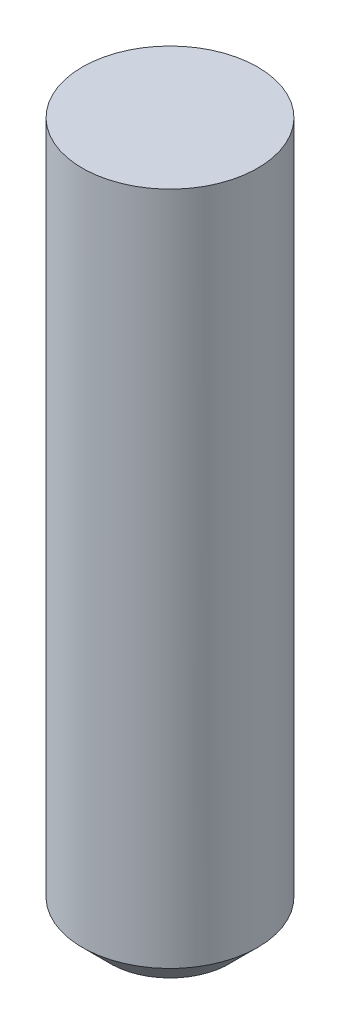
SolidWorks part; units mm, degrees
material "AISI 1020"
ref_plane "Front Plane" through (0, 0, 0) normal (0, 0, 1) x (1, 0, 0)
ref_plane "Top Plane" through (0, 0, 0) normal (0, 1, 0) x (1, 0, 0)
ref_plane "Right Plane" through (0, 0, 0) normal (1, 0, 0) x (0, 0, -1)
ref_plane "Plane1" through (0, 0, 0) normal (0, 0, -1) x (-1, 0, 0)
sketch "Sketch1" plane through (0, 0, 0) normal (0, 0, -1) x (-1, 0, 0)
  line L0 (-1.0757, 0) -> (0, 0)
  line L1 (0, 0) -> (0, 25.4)
  line L2 (0, 25.4) -> (-1.0757, 25.4)
  line L3 (-1.0757, 25.4) -> (-1.5837, 24.892)
  line L4 (-1.5837, 24.892) -> (-1.5837, 0.508)
  line L5 (-1.5837, 0.508) -> (-1.0757, 0)
  line L6 (0, 0) -> (0, 25.4) construction
revolve "Revolve1" add sketch "Sketch1" angle 360 about L6
sketch "Sketch2" plane through (0, 0, 0) normal (0, 0, 1) x (1, 0, 0)
  line L0 (1.0757, 25.4) -> (-1.0757, 25.4) construction
  line L1 (2.5475, 12.7) -> (-3.022, 12.7)
  line L2 (2.5475, 12.7) -> (2.5475, 27.0543)
  line L3 (2.5475, 27.0543) -> (-3.022, 27.0543)
  line L4 (-3.022, 12.7) -> (-3.022, 27.0543)
  dimension "D1" = 12.7
extrude "Cut-Extrude1" cut sketch "Sketch2" against normal through all both and the other way through all
